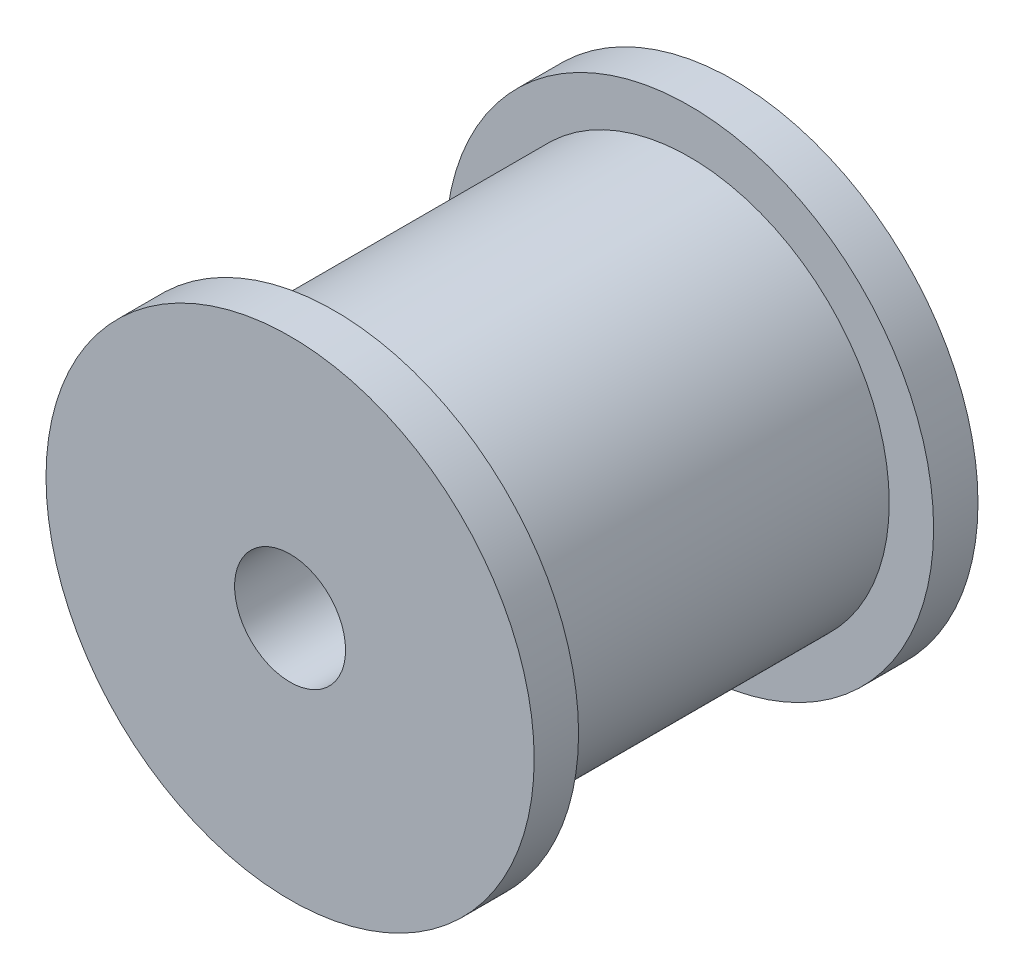
SolidWorks part; units mm, degrees
ref_plane "Спереди" through (0, 0, 0) normal (0, 0, 1) x (1, 0, 0)
ref_plane "Сверху" through (0, 0, 0) normal (0, 1, 0) x (1, 0, 0)
ref_plane "Справа" through (0, 0, 0) normal (1, 0, 0) x (0, 0, -1)
sketch "Эскиз1" plane through (0, 0, 0) normal (0, 0, 1) x (1, 0, 0)
  circle A0 centre (0, 0) radius 11
  dimension "D1" = 22
extrude "Бобышка-Вытянуть1" add sketch "Эскиз1" along normal blind 2
sketch "Эскиз2" plane through (0, 0, 2) normal (0, 0, 1) x (1, 0, 0)
  circle A0 centre (0, 0) radius 9
  dimension "D1" = 18
extrude "Бобышка-Вытянуть2" add sketch "Эскиз2" along normal blind 16
sketch "Эскиз3" plane through (0, 0, 18) normal (0, 0, 1) x (1, 0, 0)
  circle A0 centre (0, 0) radius 11
  dimension "D1" = 22
extrude "Бобышка-Вытянуть3" add sketch "Эскиз3" along normal blind 2
sketch "Эскиз4" plane through (0, 0, 20) normal (0, 0, 1) x (1, 0, 0)
  circle A0 centre (0, 0) radius 2.5
  dimension "D1" = 5
extrude "Вырез-Вытянуть1" cut sketch "Эскиз4" against normal through all contours A0
